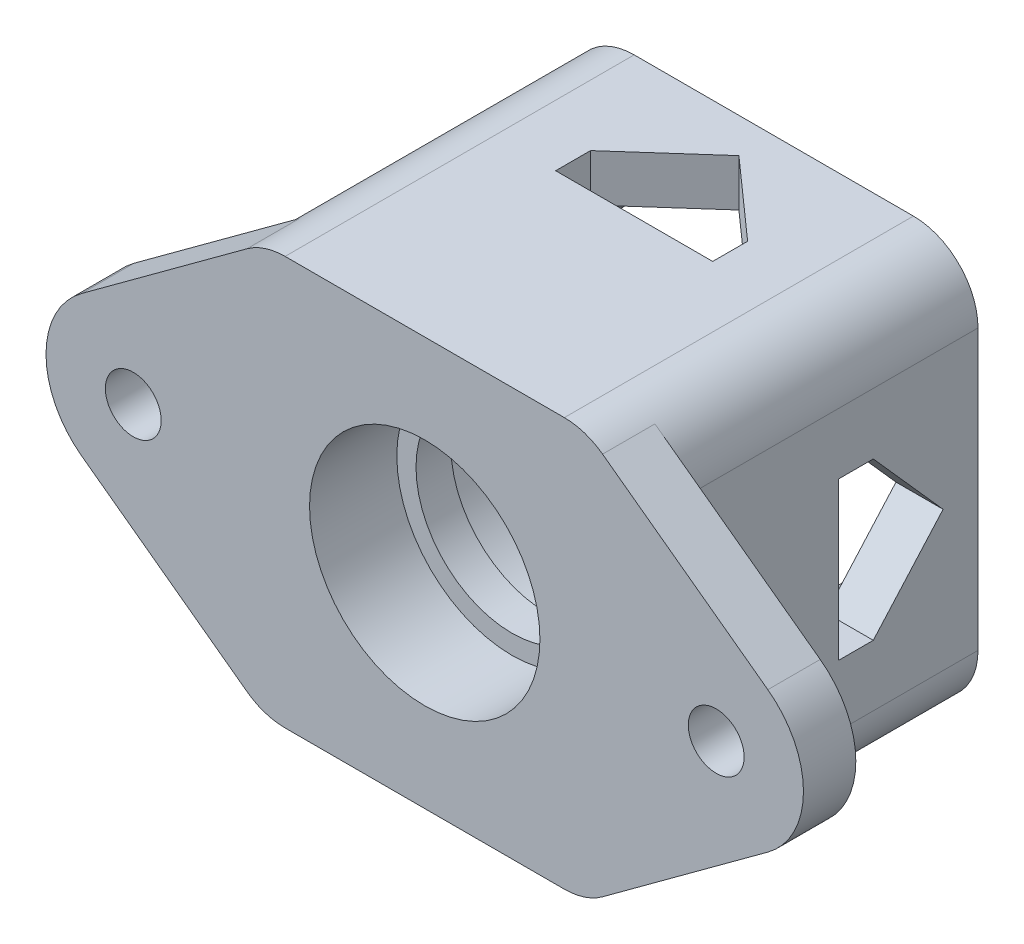
SolidWorks part; units mm, degrees
ref_plane "Front Plane" through (0, 0, 0) normal (0, 0, 1) x (1, 0, 0)
ref_plane "Top Plane" through (0, 0, 0) normal (0, 1, 0) x (1, 0, 0)
ref_plane "Right Plane" through (0, 0, 0) normal (1, 0, 0) x (0, 0, -1)
sketch "Sketch1" plane through (0, 0, 0) normal (0, 0, 1) x (1, 0, 0)
  line L0 (0, 8) -> (0, 11.7) construction
  line L1 (-8, -11.7) -> (8, -11.7)
  line L2 (-11.7, -8) -> (-11.7, 8)
  line L3 (-8, 11.7) -> (8, 11.7)
  line L4 (11.7, -8) -> (11.7, 8)
  line L5 (-8, 8) -> (8, 8)
  line L6 (-8, 8) -> (-8, -8)
  line L7 (-8, -8) -> (8, -8)
  line L8 (8, 8) -> (8, -8)
  line L9 (8, 0) -> (11.7, 0) construction
  line L10 (8, 8) -> (-8, -8) construction
  line L12 (8, -8) -> (-8, 8) construction
  circle A0 centre (-8, 8) radius 1.5
  circle A1 centre (8, 8) radius 1.5
  circle A2 centre (8, -8) radius 1.5
  circle A3 centre (-8, -8) radius 1.5
  arc A4 (-11.7, 8) -> (-8, 11.7) centre (-8, 8) cw
  arc A5 (-8, -11.7) -> (-11.7, -8) centre (-8, -8) cw
  arc A6 (8, -11.7) -> (11.7, -8) centre (8, -8) ccw
  arc A7 (8, 11.7) -> (11.7, 8) centre (8, 8) cw
  arc A8 (-8, 4.5) -> (-4.5, 8) centre (-8, 8) ccw
  arc A9 (4.5, 8) -> (8, 4.5) centre (8, 8) ccw
  arc A10 (8, -4.5) -> (4.5, -8) centre (8, -8) ccw
  arc A11 (-4.5, -8) -> (-8, -4.5) centre (-8, -8) ccw
  point P24 (0, 0)
  dimension "D3" = 3
  dimension "D4" = 3
  dimension "D5" = 3
  dimension "D6" = 3
  dimension "D7" = 3.7
  dimension "D1" = 7
  dimension "D10" = 7
  dimension "D11" = 7
  dimension "D12" = 7
  dimension "D2" = 16
  dimension "D8" = 23.4
  dimension "D9" = 23.4
extrude "Boss-Extrude1" add sketch "Sketch1" along normal blind 8 contours A7 L3 A4 L2 A5 L1 A6 L4 A3 L6 A0 L5 A1 L8 A2 L7 | L6 A8 L5 A0 | L5 A9 L8 A1 | L8 A10 L7 A2 | L7 A11 L6 A3
sketch "Sketch2" plane through (0, 0, 8) normal (0, 0, 1) x (1, 0, 0)
  line L4 (8, 11.7) -> (-8, 11.7)
  line L5 (-11.7, 8) -> (-11.7, -8)
  line L6 (-8, -11.7) -> (8, -11.7)
  line L7 (11.7, -8) -> (11.7, 8)
  line L8 (8, 11.7) -> (-8, 11.7)
  line L9 (-11.7, 8) -> (-11.7, -8)
  line L10 (-8, -11.7) -> (8, -11.7)
  line L11 (11.7, -8) -> (11.7, 8)
  circle A0 centre (0, 0) radius 5.5
  arc A4 (11.7, 8) -> (8, 11.7) centre (8, 8) ccw
  arc A5 (-8, 11.7) -> (-11.7, 8) centre (-8, 8) ccw
  arc A6 (-11.7, -8) -> (-8, -11.7) centre (-8, -8) ccw
  arc A7 (8, -11.7) -> (11.7, -8) centre (8, -8) ccw
  arc A8 (11.7, 8) -> (8, 11.7) centre (8, 8) ccw
  arc A9 (-8, 11.7) -> (-11.7, 8) centre (-8, 8) ccw
  arc A10 (-11.7, -8) -> (-8, -11.7) centre (-8, -8) ccw
  arc A11 (8, -11.7) -> (11.7, -8) centre (8, -8) ccw
  dimension "D2" = 11
  dimension "D1" = 0
extrude "Boss-Extrude2" add sketch "Sketch2" along normal blind 7
sketch "Sketch3" plane through (0, 0, 15) normal (0, 0, 1) x (1, 0, 0)
  line L4 (8, 11.7) -> (-8, 11.7)
  line L5 (-11.7, 8) -> (-11.7, -8)
  line L6 (-8, -11.7) -> (8, -11.7)
  line L7 (11.7, -8) -> (11.7, 8)
  line L8 (8, 11.7) -> (-8, 11.7)
  line L9 (-11.7, 8) -> (-11.7, -8)
  line L10 (-8, -11.7) -> (8, -11.7)
  line L11 (11.7, -8) -> (11.7, 8)
  circle A0 centre (0, 0) radius 6.6
  arc A5 (11.7, 8) -> (8, 11.7) centre (8, 8) ccw
  arc A6 (-8, 11.7) -> (-11.7, 8) centre (-8, 8) ccw
  arc A7 (-11.7, -8) -> (-8, -11.7) centre (-8, -8) ccw
  arc A8 (8, -11.7) -> (11.7, -8) centre (8, -8) ccw
  arc A9 (11.7, 8) -> (8, 11.7) centre (8, 8) ccw
  arc A10 (-8, 11.7) -> (-11.7, 8) centre (-8, 8) ccw
  arc A11 (-11.7, -8) -> (-8, -11.7) centre (-8, -8) ccw
  arc A12 (8, -11.7) -> (11.7, -8) centre (8, -8) ccw
  dimension "D1" = 13.2
  dimension "D2" = 0
extrude "Boss-Extrude3" add sketch "Sketch3" along normal blind 5
sketch "Sketch5" plane through (0, -11.7, 0) normal (0, -1, 0) x (1, 0, 0)
  line L0 (0, 0) -> (0, 2) construction
  line L1 (-8, 0) -> (8, 0) construction
  line L2 (-4.5, 6) -> (0, 2)
  line L3 (0, 2) -> (4.5, 6)
  line L4 (4.5, 8) -> (-4.5, 8)
  line L5 (0, 8) -> (0, 20) construction
  line L6 (-8, 20) -> (8, 20) construction
  line L7 (4.5, 8) -> (4.5, 6)
  line L9 (-4.5, 8) -> (-4.5, 6)
  line L11 (-4.5, 6) -> (4.5, 6) construction
  dimension "D1" = 2
  dimension "D2" = 2
  dimension "D3" = 9
extrude "Cut-Extrude2" cut sketch "Sketch5" against normal through all
sketch "Sketch6" plane through (0, 0, 8) normal (0, 0, -1) x (-1, 0, 0)
  circle A0 centre (0, 0) radius 6.6
  dimension "D1" = 13.2
extrude "Cut-Extrude3" cut sketch "Sketch6" against normal blind 5
sketch "Sketch7" plane through (0, 0, 20) normal (0, 0, 1) x (1, 0, 0)
  line L0 (11.7, 0) -> (16.7, 0) construction
  line L1 (11.7, -8) -> (11.7, 8) construction
  line L2 (19.659, 4.0304) -> (10.1897, 10.9825)
  line L3 (19.659, -4.0304) -> (10.1897, -10.9825)
  line L4 (0, 0) -> (0, 11.7) construction
  line L5 (8, 11.7) -> (-8, 11.7) construction
  line L6 (8, 11.7) -> (-8, 11.7)
  line L7 (-11.7, 8) -> (-11.7, -8)
  line L8 (-8, -11.7) -> (8, -11.7)
  line L9 (11.7, -8) -> (11.7, 8)
  line L13 (11.7, -8) -> (11.7, 8)
  line L14 (-11.7, -8) -> (-11.7, 8)
  line L15 (-19.659, -4.0304) -> (-10.1897, -10.9825)
  line L16 (-19.659, 4.0304) -> (-10.1897, 10.9825)
  line L17 (-11.7, 0) -> (-16.7, 0) construction
  circle A0 centre (16.7, 0) radius 1.6
  arc A1 (19.659, -4.0304) -> (19.659, 4.0304) centre (16.7, 0) ccw
  arc A2 (-10.1897, -10.9825) -> (-11.7, -8) centre (-8, -8) cw
  arc A3 (-11.7, 8) -> (-10.1897, 10.9825) centre (-8, 8) cw
  arc A4 (-19.659, -4.0304) -> (-19.659, 4.0304) centre (-16.7, 0) cw
  circle A5 centre (-16.7, 0) radius 1.6
  arc A6 (11.7, 8) -> (8, 11.7) centre (8, 8) ccw
  arc A7 (-8, 11.7) -> (-11.7, 8) centre (-8, 8) ccw
  arc A8 (-11.7, -8) -> (-8, -11.7) centre (-8, -8) ccw
  arc A9 (8, -11.7) -> (11.7, -8) centre (8, -8) ccw
  arc A10 (11.7, 8) -> (10.1897, 10.9825) centre (8, 8) ccw
  arc A13 (10.1897, -10.9825) -> (11.7, -8) centre (8, -8) ccw
  dimension "D2" = 3.2
  dimension "D3" = 10
  dimension "D1" = 5
  dimension "D4" = 0
extrude "Boss-Extrude4" add sketch "Sketch7" against normal blind 3
pattern_circular "CirPattern1" count 2 every 90 about axis through (0, 0, 8) along (0, 0, -1) of "Cut-Extrude2"
sketch "Sketch8" plane through (0, 0, 0) normal (0, 0, -1) x (-1, 0, 0)
  line L8 (-8, 4.5) -> (-8, -4.5) construction
  line L9 (4.5, -8) -> (-4.5, -8) construction
  line L10 (8, 4.5) -> (8, -4.5) construction
  line L11 (4.5, 8) -> (-4.5, 8) construction
  line L12 (-8, 4.5) -> (-8, -4.5)
  line L13 (4.5, -8) -> (-4.5, -8)
  line L14 (8, 4.5) -> (8, -4.5)
  line L15 (4.5, 8) -> (-4.5, 8)
  arc A8 (-8, 4.5) -> (-4.5, 8) centre (-8, 8) ccw construction
  arc A9 (-4.5, -8) -> (-8, -4.5) centre (-8, -8) ccw construction
  arc A10 (8, -4.5) -> (4.5, -8) centre (8, -8) ccw construction
  arc A11 (4.5, 8) -> (8, 4.5) centre (8, 8) ccw construction
  arc A12 (-8, 4.5) -> (-4.5, 8) centre (-8, 8) ccw
  arc A13 (-4.5, -8) -> (-8, -4.5) centre (-8, -8) ccw
  arc A14 (8, -4.5) -> (4.5, -8) centre (8, -8) ccw
  arc A15 (4.5, 8) -> (8, 4.5) centre (8, 8) ccw
extrude "Cut-Extrude-Thin1" cut sketch "Sketch8" against normal up to surface (8 mm away) thin
